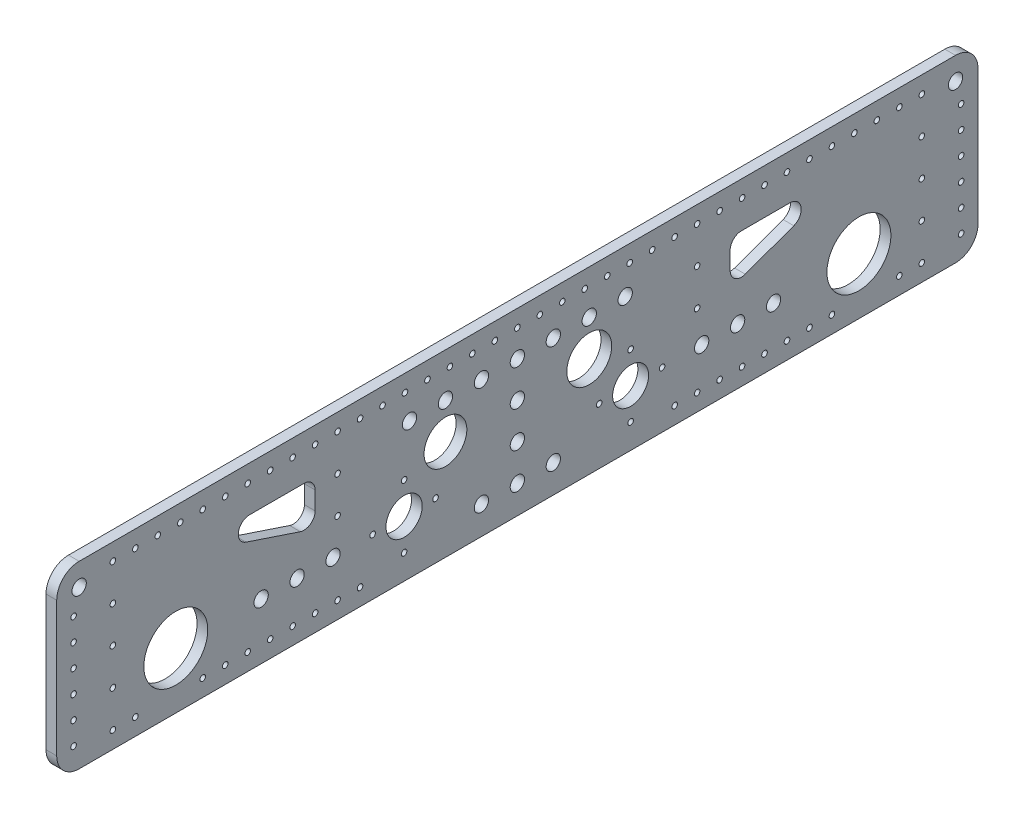
SolidWorks part; units mm, degrees
ref_plane "Front Plane" through (0, 0, 0) normal (0, 0, 1) x (1, 0, 0)
ref_plane "Top Plane" through (0, 0, 0) normal (0, 1, 0) x (1, 0, 0)
ref_plane "Right Plane" through (0, 0, 0) normal (1, 0, 0) x (0, 0, -1)
sketch "Sketch2" plane through (0, 0, 0) normal (1, 0, 0) x (0, 0, -1)
  line L0 (-23.4723, 28.6683) -> (-23.4723, -31.3317)
  line L1 (-13.4723, 38.6683) -> (376.5277, 38.6683)
  line L2 (-13.4723, -41.3317) -> (376.5277, -41.3317)
  line L3 (386.5277, 28.6683) -> (386.5277, -31.3317)
  line L4 (91.5277, 13.6683) -> (91.5277, 5.6054)
  line L5 (86.5277, 18.6683) -> (62.3391, 18.6683)
  line L10 (276.2352, 13.6683) -> (276.2352, 5.8068)
  line L11 (281.2352, 18.6683) -> (302.8543, 18.6683)
  line L15 (84.9465, 0.862) -> (60.7579, 8.9249)
  line L21 (304.563, 8.9693) -> (282.9439, 1.1078)
  circle A1 centre (29.5277, -16.3317) radius 14.225
  circle A2 centre (333.5277, -16.3317) radius 14.225
  arc A15 (-23.4723, 28.6683) -> (-13.4723, 38.6683) centre (-13.4723, 28.6683) cw
  arc A16 (-13.4723, -41.3317) -> (-23.4723, -31.3317) centre (-13.4723, -31.3317) cw
  arc A17 (386.5277, 28.6683) -> (376.5277, 38.6683) centre (376.5277, 28.6683) ccw
  arc A18 (376.5277, -41.3317) -> (386.5277, -31.3317) centre (376.5277, -31.3317) ccw
  circle A59 centre (181.5277, -28.7717) radius 3.18
  circle A60 centre (197.5277, -28.7717) radius 3.18
  circle A63 centre (197.5277, 19.2283) radius 3.18
  circle A64 centre (181.5277, -12.7717) radius 3.18
  circle A65 centre (181.5277, 3.2283) radius 3.18
  circle A66 centre (181.5277, 19.2283) radius 3.18
  circle A67 centre (165.5277, -28.7717) radius 3.18
  circle A68 centre (165.5277, 19.2283) radius 3.18
  circle A69 centre (197.5277, -12.7717) radius 3.18 [skipped]
  circle A70 centre (197.5277, 3.2283) radius 3.18 [skipped]
  circle A71 centre (-8.4723, 31.1683) radius 1.25 construction
  circle A150 centre (83.5027, -16.3317) radius 3.18
  circle A151 centre (279.5527, -16.3317) radius 3.18
  circle A152 centre (1.5277, 31.1683) radius 1.25
  circle A153 centre (11.5277, 31.1683) radius 1.25
  circle A154 centre (21.5277, 31.1683) radius 1.25
  circle A155 centre (31.5277, 31.1683) radius 1.25
  circle A156 centre (41.5277, 31.1683) radius 1.25
  circle A157 centre (51.5277, 31.1683) radius 1.25
  circle A158 centre (61.5277, 31.1683) radius 1.25
  circle A159 centre (71.5277, 31.1683) radius 1.25
  circle A160 centre (81.5277, 31.1683) radius 1.25
  circle A161 centre (91.5277, 31.1683) radius 1.25
  circle A162 centre (101.5277, 31.1683) radius 1.25
  circle A163 centre (111.5277, 31.1683) radius 1.25
  circle A164 centre (121.5277, 31.1683) radius 1.25
  circle A165 centre (131.5277, 31.1683) radius 1.25
  circle A166 centre (141.5277, 31.1683) radius 1.25
  circle A167 centre (151.5277, 31.1683) radius 1.25
  circle A168 centre (161.5277, 31.1683) radius 1.25
  circle A169 centre (171.5277, 31.1683) radius 1.25
  circle A170 centre (181.5277, 31.1683) radius 1.25
  circle A171 centre (191.5277, 31.1683) radius 1.25
  circle A172 centre (201.5277, 31.1683) radius 1.25
  circle A173 centre (211.5277, 31.1683) radius 1.25
  circle A174 centre (221.5277, 31.1683) radius 1.25
  circle A175 centre (231.5277, 31.1683) radius 1.25
  circle A176 centre (241.5277, 31.1683) radius 1.25
  circle A177 centre (251.5277, 31.1683) radius 1.25
  circle A178 centre (261.5277, 31.1683) radius 1.25
  circle A179 centre (271.5277, 31.1683) radius 1.25
  circle A180 centre (281.5277, 31.1683) radius 1.25
  circle A181 centre (291.5277, 31.1683) radius 1.25
  circle A182 centre (301.5277, 31.1683) radius 1.25
  circle A183 centre (311.5277, 31.1683) radius 1.25
  circle A184 centre (321.5277, 31.1683) radius 1.25
  circle A185 centre (331.5277, 31.1683) radius 1.25
  circle A186 centre (341.5277, 31.1683) radius 1.25
  circle A187 centre (351.5277, 31.1683) radius 1.25
  circle A188 centre (361.5277, 31.1683) radius 1.25
  circle A190 centre (1.5277, -33.8317) radius 1.25
  circle A191 centre (11.5277, -33.8317) radius 1.25
  circle A194 centre (41.5277, -33.8317) radius 1.25
  circle A195 centre (51.5277, -33.8317) radius 1.25
  circle A196 centre (61.5277, -33.8317) radius 1.25
  circle A197 centre (71.5277, -33.8317) radius 1.25
  circle A198 centre (81.5277, -33.8317) radius 1.25
  circle A199 centre (91.5277, -33.8317) radius 1.25
  circle A200 centre (101.5277, -33.8317) radius 1.25
  circle A201 centre (111.5277, -33.8317) radius 1.25
  circle A215 centre (251.5277, -33.8317) radius 1.25
  circle A216 centre (261.5277, -33.8317) radius 1.25
  circle A217 centre (271.5277, -33.8317) radius 1.25
  circle A218 centre (281.5277, -33.8317) radius 1.25
  circle A219 centre (291.5277, -33.8317) radius 1.25
  circle A220 centre (301.5277, -33.8317) radius 1.25
  circle A221 centre (311.5277, -33.8317) radius 1.25
  circle A222 centre (321.5277, -33.8317) radius 1.25
  circle A225 centre (351.5277, -33.8317) radius 1.25
  circle A226 centre (361.5277, -33.8317) radius 1.25
  circle A229 centre (181.5277, -33.8317) radius 1.25 [skipped]
  circle A230 centre (201.5277, -33.8317) radius 1.25 [skipped]
  circle A231 centre (161.5277, -33.8317) radius 1.25 [skipped]
  circle A232 centre (151.5277, -33.8317) radius 1.25 [skipped]
  circle A233 centre (141.5277, -33.8317) radius 1.25 [skipped]
  circle A234 centre (131.5277, -33.8317) radius 1.25 [skipped]
  circle A235 centre (171.5277, -33.8317) radius 1.25 [skipped]
  circle A236 centre (191.5277, -33.8317) radius 1.25 [skipped]
  circle A237 centre (211.5277, -33.8317) radius 1.25 [skipped]
  circle A238 centre (221.5277, -33.8317) radius 1.25 [skipped]
  circle A239 centre (231.5277, -33.8317) radius 1.25 [skipped]
  circle A240 centre (31.5277, -33.8317) radius 1.25 [skipped]
  circle A241 centre (21.5277, -33.8317) radius 1.25 [skipped]
  circle A242 centre (331.5277, -33.8317) radius 1.25 [skipped]
  circle A243 centre (341.5277, -33.8317) radius 1.25 [skipped]
  circle A245 centre (-13.4723, 28.6683) radius 3.18
  circle A247 centre (376.5277, 28.6683) radius 3.18
  circle A248 centre (371.5277, 31.1683) radius 1.25 [skipped]
  circle A249 centre (371.5277, -33.8317) radius 1.25 [skipped]
  circle A250 centre (-8.4723, -33.8317) radius 1.25 [skipped]
  circle A254 centre (295.5527, -16.3317) radius 3.18
  circle A255 centre (67.5027, -16.3317) radius 3.18
  circle A256 centre (263.5527, -16.3317) radius 3.18
  circle A257 centre (121.5277, -33.8317) radius 1.25 [skipped]
  circle A260 centre (131.1277, -30.3317) radius 1.25
  circle A261 centre (145.1277, -16.3317) radius 1.25
  circle A262 centre (131.1277, -2.3317) radius 1.25
  circle A263 centre (117.1277, -16.3317) radius 1.25
  circle A264 centre (231.9277, -30.3317) radius 1.25
  circle A265 centre (217.9277, -16.3317) radius 1.25
  circle A266 centre (231.9277, -2.3317) radius 1.25
  circle A267 centre (245.9277, -16.3317) radius 1.25
  circle A268 centre (231.9277, -16.3317) radius 8
  circle A269 centre (131.1277, -16.3317) radius 8.0683
  circle A270 centre (241.5277, -33.8317) radius 1.25 [skipped]
  circle A271 centre (-15.9723, 18.6683) radius 1.25
  circle A272 centre (379.0277, 18.6683) radius 1.25
  circle A273 centre (379.0277, 8.6683) radius 1.25
  circle A274 centre (379.0277, -1.3317) radius 1.25
  circle A275 centre (379.0277, -11.3317) radius 1.25
  circle A276 centre (379.0277, -21.3317) radius 1.25
  circle A277 centre (379.0277, -31.3317) radius 1.25
  circle A278 centre (-15.9723, 8.6683) radius 1.25
  circle A279 centre (-15.9723, -1.3317) radius 1.25
  circle A280 centre (-15.9723, -11.3317) radius 1.25
  circle A281 centre (-15.9723, -21.3317) radius 1.25
  circle A282 centre (-15.9723, -31.3317) radius 1.25
  circle A284 centre (101.5277, -1.3317) radius 1.25
  circle A285 centre (101.5277, 14.9183) radius 1.25
  arc A286 (101.4697, -18.8304) -> (102.6179, -16.9702) centre (99.5027, -16.3317) ccw [skipped]
  circle A287 centre (361.5277, -17.5817) radius 1.25
  circle A288 centre (361.5277, -1.3317) radius 1.25
  circle A289 centre (361.5277, 14.9183) radius 1.25
  circle A290 centre (1.5277, -17.5817) radius 1.25
  circle A291 centre (1.5277, -1.3317) radius 1.25
  circle A292 centre (1.5277, 14.9183) radius 1.25
  circle A293 centre (101.5277, -17.5817) radius 1.25 [skipped]
  circle A294 centre (99.5027, -16.3317) radius 3.18
  circle A298 centre (261.5277, -1.3317) radius 1.25
  circle A300 centre (261.5277, 14.9183) radius 1.25
  arc A301 (260.4374, -16.9702) -> (261.5857, -18.8304) centre (261.5277, -17.5817) ccw [skipped]
  arc A302 (80.4021, 31.712) -> (81.5373, 29.9183) centre (83.5027, 32.4183) ccw [skipped]
  circle A303 centre (83.5027, 16.1683) radius 3.18 [skipped]
  circle A304 centre (83.5027, -0.0817) radius 3.18 [skipped]
  circle A305 centre (149.5277, 19.2283) radius 3.18
  circle A306 centre (133.5277, 19.2283) radius 3.18
  circle A307 centre (213.5277, 19.2283) radius 3.18
  circle A308 centre (229.5277, 19.2283) radius 3.18
  circle A309 centre (149.5277, 3.2283) radius 9.5139
  circle A310 centre (213.5277, 3.2283) radius 10
  arc A311 (84.9465, 0.862) -> (91.5277, 5.6054) centre (86.5277, 5.6054) ccw
  arc A312 (60.7579, 8.9249) -> (62.3391, 18.6683) centre (62.3391, 13.6683) cw
  arc A313 (91.5277, 13.6683) -> (86.5277, 18.6683) centre (86.5277, 13.6683) ccw
  arc A314 (281.2352, 18.6683) -> (276.2352, 13.6683) centre (281.2352, 13.6683) ccw
  arc A315 (304.563, 8.9693) -> (302.8543, 18.6683) centre (302.8543, 13.6683) ccw
  arc A316 (276.2352, 5.8068) -> (282.9439, 1.1078) centre (281.2352, 5.8068) ccw
  point P32 (-23.4723, 38.6683)
  point P35 (-23.4723, -41.3317)
  point P40 (386.5277, -41.3317)
  point P123 (181.5277, -41.3317)
  dimension "D3" = 25
  dimension "D7" = 10
  dimension "D8" = 10
  dimension "D9" = 10
  dimension "D10" = 10
  dimension "D11" = 7.5
  dimension "D13" = 12.56
  dimension "D20" = 7.5
  dimension "D35" = 5
  dimension "D36" = 5
  dimension "D1" = 80
  dimension "D2" = 410
  dimension "D4" = 53
  dimension "D5" = 25
  dimension "D6" = 53
  dimension "D12" = 15
  dimension "D14" = 205
  dimension "D21" = 20
  dimension "D31" = 3
  dimension "D32" = 20
  dimension "D33" = 20
  dimension "D34" = 3
  dimension "D15" = 2
  dimension "D16" = 4
  dimension "D17" = 2
  dimension "D18" = 39
  dimension "D19" = 2
  dimension "D22" = 2
  dimension "D23" = 2
  dimension "D24" = 2
  dimension "D25" = 6
  dimension "D26" = 4
  dimension "D27" = 4
  dimension "D28" = 4
  dimension "D29" = 2
  dimension "D30" = 4
extrude "Boss-Extrude1" add sketch "Sketch2" along normal blind 4.7625
